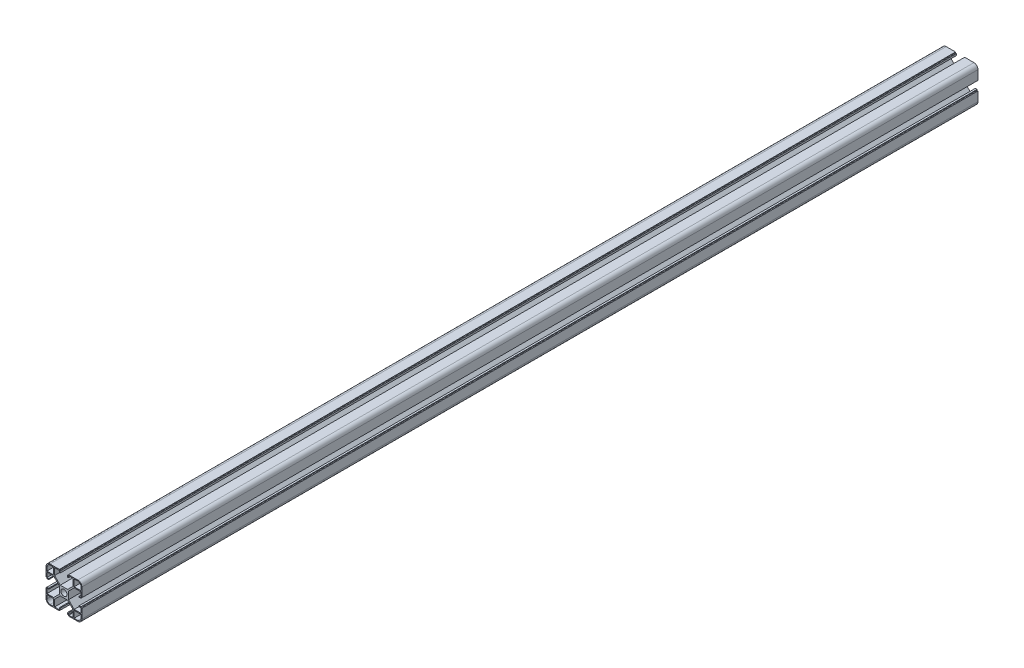
SolidWorks part; units mm, degrees
ref_plane "前视基准面" through (0, 0, 0) normal (0, 0, 1) x (1, 0, 0)
ref_plane "上视基准面" through (0, 0, 0) normal (0, 1, 0) x (1, 0, 0)
ref_plane "右视基准面" through (0, 0, 0) normal (1, 0, 0) x (0, 0, -1)
sketch "草图1" plane through (0, 0, 0) normal (0, 0, 1) x (1, 0, 0)
  line L0 (-11.1482, 14.803) -> (-21.5482, 14.803)
  line L1 (-26.0482, 10.303) -> (-26.0482, -0.097)
  line L2 (-10.1482, 13.803) -> (-10.6482, 13.803)
  line L3 (-11.1482, 11.803) -> (-11.1482, 13.303)
  line L4 (-11.6482, 13.803) -> (-16.4482, 13.803)
  line L5 (-17.4482, 13.803) -> (-21.5482, 13.803)
  line L6 (-25.0482, 10.303) -> (-25.0482, 6.203)
  line L7 (-25.0482, 5.203) -> (-25.0482, -0.097)
  line L8 (-25.0482, -0.597) -> (-25.0482, -1.097)
  line L9 (-23.0482, -0.097) -> (-23.0482, -1.097)
  line L10 (-11.2482, -1.0577) -> (-11.2482, -9.3364)
  line L11 (-10.1876, -10.397) -> (-1.9089, -10.397)
  line L12 (-0.8482, -9.3364) -> (-0.8482, -1.0577)
  line L13 (-1.9089, 0.003) -> (-10.1876, 0.003)
  line L14 (-17.5089, 5.203) -> (-25.0482, 5.203)
  line L15 (-17.4482, 6.203) -> (-25.0482, 6.203)
  line L16 (-23.0482, -1.097) -> (-25.0482, -1.097)
  line L17 (-23.0482, -0.097) -> (-25.0482, -0.097)
  line L18 (-25.5482, -0.097) -> (-26.0482, -0.097)
  line L19 (-16.4482, 13.803) -> (-16.4482, 6.2636)
  line L20 (-17.4482, 13.803) -> (-17.4482, 6.203)
  line L21 (-10.1482, 11.803) -> (-10.1482, 13.803)
  line L22 (-11.1482, 14.303) -> (-11.1482, 14.803)
  line L23 (-10.1876, 0.003) -> (-16.4482, 6.2636)
  line L24 (-11.2482, -1.0577) -> (-17.5089, 5.203)
  line L25 (-11.1482, 11.803) -> (-10.1482, 11.803)
  line L26 (-0.9482, 14.803) -> (9.4518, 14.803)
  line L27 (13.9518, 10.303) -> (13.9518, -0.097)
  line L28 (-1.9482, 13.803) -> (-1.4482, 13.803)
  line L29 (-0.9482, 11.803) -> (-0.9482, 13.303)
  line L30 (-0.4482, 13.803) -> (4.3518, 13.803)
  line L31 (5.3518, 13.803) -> (9.4518, 13.803)
  line L32 (12.9518, 10.303) -> (12.9518, 6.203)
  line L33 (12.9518, 5.203) -> (12.9518, 0.403)
  line L34 (12.4518, -0.097) -> (10.9518, -0.097)
  line L35 (12.9518, -0.597) -> (12.9518, -1.097)
  line L36 (10.9518, -0.097) -> (10.9518, -1.097)
  line L37 (5.4124, 5.203) -> (12.9518, 5.203)
  line L38 (5.3518, 6.203) -> (12.9518, 6.203)
  line L39 (10.9518, -1.097) -> (12.9518, -1.097)
  line L40 (13.4518, -0.097) -> (13.9518, -0.097)
  line L41 (4.3518, 13.803) -> (4.3518, 6.2636)
  line L42 (5.3518, 13.803) -> (5.3518, 6.203)
  line L43 (-1.9482, 11.803) -> (-1.9482, 13.803)
  line L44 (-0.9482, 14.303) -> (-0.9482, 14.803)
  line L45 (-1.9089, 0.003) -> (4.3518, 6.2636)
  line L46 (-0.8482, -1.0577) -> (5.4124, 5.203)
  line L47 (-0.9482, 11.803) -> (-1.9482, 11.803)
  line L48 (-11.1482, -25.197) -> (-21.5482, -25.197)
  line L49 (-26.0482, -20.697) -> (-26.0482, -10.297)
  line L50 (-10.1482, -24.197) -> (-10.6482, -24.197)
  line L51 (-11.1482, -22.197) -> (-11.1482, -23.697)
  line L52 (-11.6482, -24.197) -> (-16.4482, -24.197)
  line L53 (-17.4482, -24.197) -> (-21.5482, -24.197)
  line L54 (-25.0482, -20.697) -> (-25.0482, -16.597)
  line L55 (-25.0482, -15.597) -> (-25.0482, -10.797)
  line L56 (-24.5482, -10.297) -> (-23.0482, -10.297)
  line L57 (-25.0482, -9.797) -> (-25.0482, -9.297)
  line L58 (-23.0482, -10.297) -> (-23.0482, -9.297)
  line L59 (-17.5089, -15.597) -> (-25.0482, -15.597)
  line L60 (-17.4482, -16.597) -> (-25.0482, -16.597)
  line L61 (-23.0482, -9.297) -> (-25.0482, -9.297)
  line L62 (-25.5482, -10.297) -> (-26.0482, -10.297)
  line L63 (-16.4482, -24.197) -> (-16.4482, -16.6577)
  line L64 (-17.4482, -24.197) -> (-17.4482, -16.597)
  line L65 (-10.1482, -22.197) -> (-10.1482, -24.197)
  line L66 (-11.1482, -24.697) -> (-11.1482, -25.197)
  line L67 (-10.1876, -10.397) -> (-16.4482, -16.6577)
  line L68 (-11.2482, -9.3364) -> (-17.5089, -15.597)
  line L69 (-11.1482, -22.197) -> (-10.1482, -22.197)
  line L70 (-0.9482, -25.197) -> (9.4518, -25.197)
  line L71 (13.9518, -20.697) -> (13.9518, -10.297)
  line L72 (-1.9482, -24.197) -> (-1.4482, -24.197)
  line L73 (-0.9482, -22.197) -> (-0.9482, -23.697)
  line L74 (-0.4482, -24.197) -> (4.3518, -24.197)
  line L75 (5.3518, -24.197) -> (9.4518, -24.197)
  line L76 (12.9518, -20.697) -> (12.9518, -16.597)
  line L77 (12.9518, -15.597) -> (12.9518, -10.797)
  line L78 (12.4518, -10.297) -> (10.9518, -10.297)
  line L79 (12.9518, -9.797) -> (12.9518, -9.297)
  line L80 (10.9518, -10.297) -> (10.9518, -9.297)
  line L81 (5.4124, -15.597) -> (12.9518, -15.597)
  line L82 (5.3518, -16.597) -> (12.9518, -16.597)
  line L83 (10.9518, -9.297) -> (12.9518, -9.297)
  line L84 (13.4518, -10.297) -> (13.9518, -10.297)
  line L85 (4.3518, -24.197) -> (4.3518, -16.6577)
  line L86 (5.3518, -24.197) -> (5.3518, -16.597)
  line L87 (-1.9482, -22.197) -> (-1.9482, -24.197)
  line L88 (-0.9482, -24.697) -> (-0.9482, -25.197)
  line L89 (-1.9089, -10.397) -> (4.3518, -16.6577)
  line L90 (-0.8482, -9.3364) -> (5.4124, -15.597)
  line L91 (-0.9482, -22.197) -> (-1.9482, -22.197)
  arc A0 (-21.5482, 14.803) -> (-26.0482, 10.303) centre (-21.5482, 10.303) ccw
  arc A1 (-11.1482, 13.303) -> (-11.6482, 13.803) centre (-11.6482, 13.303) ccw
  arc A2 (-21.5482, 13.803) -> (-25.0482, 10.303) centre (-21.5482, 10.303) ccw
  circle A3 centre (-6.0482, -5.197) radius 3.4
  arc A4 (-11.1482, 14.303) -> (-10.6482, 13.803) centre (-10.6482, 14.303) ccw
  arc A5 (-25.0482, -0.597) -> (-25.5482, -0.097) centre (-25.5482, -0.597) ccw
  arc A6 (13.9518, 10.303) -> (9.4518, 14.803) centre (9.4518, 10.303) ccw
  arc A7 (-0.4482, 13.803) -> (-0.9482, 13.303) centre (-0.4482, 13.303) ccw
  arc A8 (12.9518, 10.303) -> (9.4518, 13.803) centre (9.4518, 10.303) ccw
  arc A9 (12.4518, -0.097) -> (12.9518, 0.403) centre (12.4518, 0.403) ccw
  arc A10 (-1.4482, 13.803) -> (-0.9482, 14.303) centre (-1.4482, 14.303) ccw
  arc A11 (13.4518, -0.097) -> (12.9518, -0.597) centre (13.4518, -0.597) ccw
  arc A12 (-26.0482, -20.697) -> (-21.5482, -25.197) centre (-21.5482, -20.697) ccw
  arc A13 (-11.6482, -24.197) -> (-11.1482, -23.697) centre (-11.6482, -23.697) ccw
  arc A14 (-25.0482, -20.697) -> (-21.5482, -24.197) centre (-21.5482, -20.697) ccw
  arc A15 (-24.5482, -10.297) -> (-25.0482, -10.797) centre (-24.5482, -10.797) ccw
  arc A16 (-10.6482, -24.197) -> (-11.1482, -24.697) centre (-10.6482, -24.697) ccw
  arc A17 (-25.5482, -10.297) -> (-25.0482, -9.797) centre (-25.5482, -9.797) ccw
  arc A18 (9.4518, -25.197) -> (13.9518, -20.697) centre (9.4518, -20.697) ccw
  arc A19 (-0.9482, -23.697) -> (-0.4482, -24.197) centre (-0.4482, -23.697) ccw
  arc A20 (9.4518, -24.197) -> (12.9518, -20.697) centre (9.4518, -20.697) ccw
  arc A21 (12.9518, -10.797) -> (12.4518, -10.297) centre (12.4518, -10.797) ccw
  arc A22 (-0.9482, -24.697) -> (-1.4482, -24.197) centre (-1.4482, -24.697) ccw
  arc A23 (12.9518, -9.797) -> (13.4518, -10.297) centre (13.4518, -9.797) ccw
extrude "凸台-拉伸1" add sketch "草图1" along normal blind 1000
